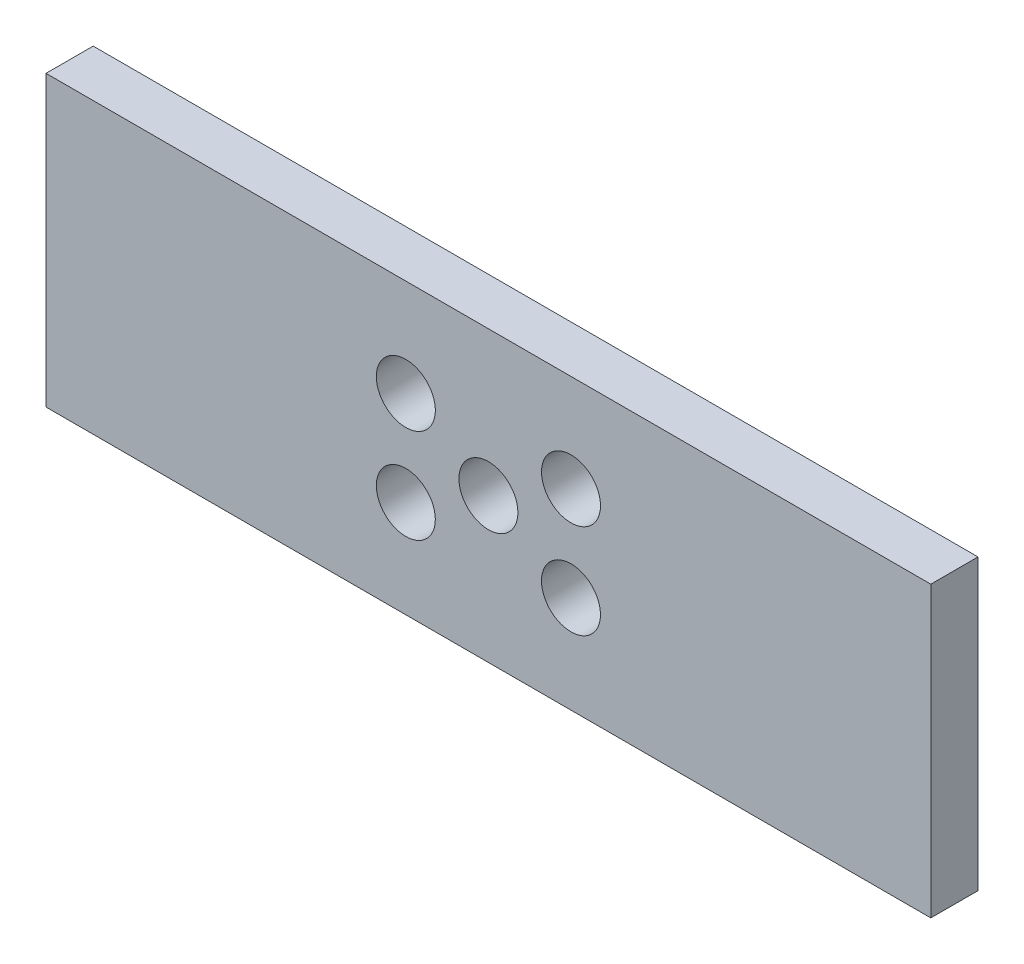
SolidWorks part; units mm, degrees
ref_plane "Alzado" through (0, 0, 0) normal (0, 0, 1) x (1, 0, 0)
ref_plane "Planta" through (0, 0, 0) normal (0, 1, 0) x (1, 0, 0)
ref_plane "Vista lateral" through (0, 0, 0) normal (1, 0, 0) x (0, 0, -1)
sketch "Croquis1" plane through (0, 0, 0) normal (0, 0, 1) x (1, 0, 0)
  line L0 (0, 0) -> (4, 0) construction
  line L1 (37.5, 12.25) -> (-37.5, 12.25)
  line L2 (37.5, 12.25) -> (37.5, -12.25)
  line L3 (37.5, -12.25) -> (-37.5, -12.25)
  line L4 (-37.5, 12.25) -> (-37.5, -12.25)
  line L5 (37.5, 12.25) -> (-37.5, -12.25) construction
  line L6 (37.5, -12.25) -> (-37.5, 12.25) construction
  line L7 (0, 12.25) -> (0, -12.25) construction
  line L8 (4, 12.25) -> (4, -12.25) construction
  line L9 (-37.5, 4) -> (37.5, 4) construction
  line L10 (0, 0) -> (4, 4) construction
  line L11 (-37.5, 0) -> (37.5, 0) construction
  line L12 (7, 12.25) -> (7, -12.25) construction
  line L13 (-37.5, -4) -> (37.5, -4) construction
  circle A0 centre (0, 0) radius 2.5
  circle A3 centre (7, 4) radius 2.5
  circle A4 centre (7, -4) radius 2.5
  circle A5 centre (-7, -4) radius 2.5
  circle A6 centre (-7, 4) radius 2.5
  point P0 (0, 0)
  dimension "D1" = 7
  dimension "D2" = 8
extrude "Saliente-Extruir1" add sketch "Croquis1" along normal blind 4
